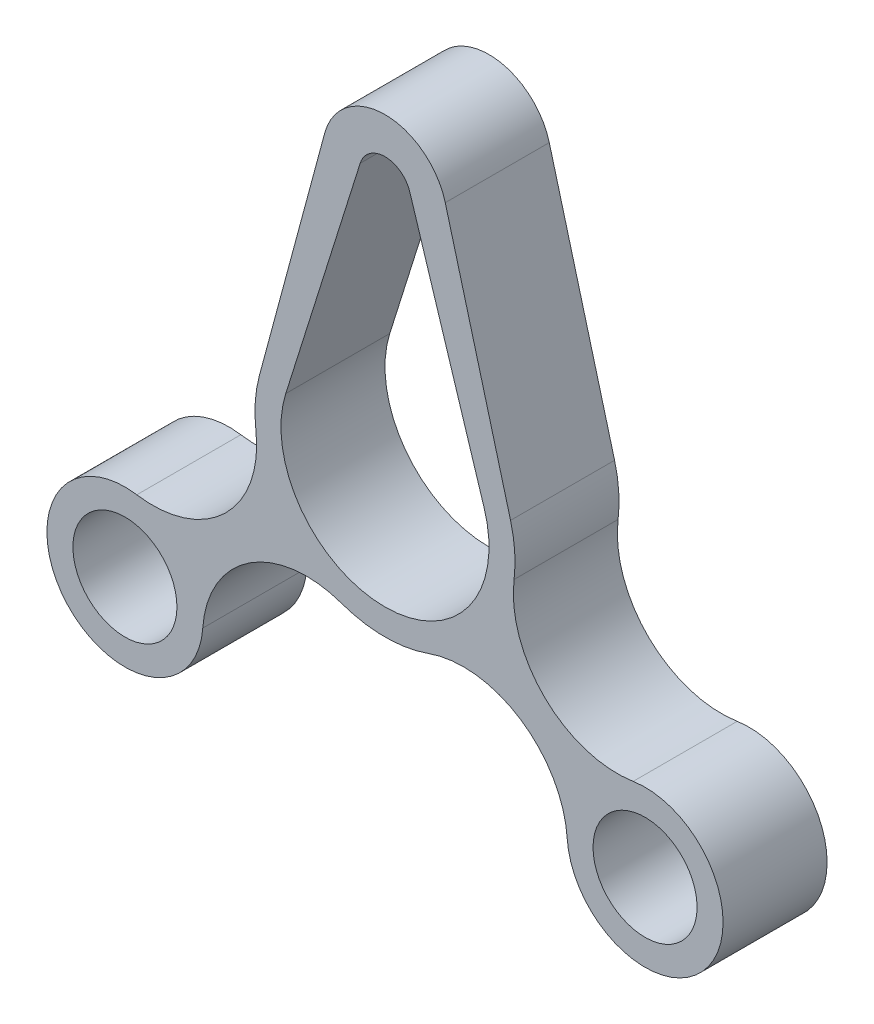
SolidWorks part; units mm, degrees
ref_plane "Front Plane" through (0, 0, 0) normal (0, 0, 1) x (1, 0, 0)
ref_plane "Top Plane" through (0, 0, 0) normal (0, 1, 0) x (1, 0, 0)
ref_plane "Right Plane" through (0, 0, 0) normal (1, 0, 0) x (0, 0, -1)
sketch "Sketch1" plane through (0, 0, 0) normal (0, 0, 1) x (1, 0, 0)
  line L0 (0, 0) -> (0, 40332.8036) construction
  line L1 (0, 0) -> (40332.8036, 0) construction
  line L2 (-24.1402, 6.5) -> (-11.5873, 53.12)
  line L3 (24.1402, 6.5) -> (11.5873, 53.12)
  line L4 (-19.0788, 6) -> (-4.7697, 51.5)
  line L5 (19.0788, 6) -> (4.7697, 51.5)
  arc A0 (-19.0788, 6) -> (19.0788, 6) centre (0, 0) ccw
  arc A1 (-24.1402, 6.5) -> (-24.8188, -3.0042) centre (0, 0) ccw
  circle A2 centre (-50, -40) radius 10
  arc A3 (-47.7174, -25.1747) -> (-35.0352, -41.0274) centre (-50, -40) ccw
  arc A4 (-47.7174, -25.1747) -> (-24.8188, -3.0042) centre (-44.6739, -5.4076) ccw
  arc A5 (4.7697, 51.5) -> (-4.7697, 51.5) centre (0, 50) ccw
  arc A6 (11.5873, 53.12) -> (-11.5873, 53.12) centre (0, 50) ccw
  arc A7 (-35.0352, -41.0274) -> (-8.379, -23.554) centre (-15.0822, -42.3973) cw
  circle A8 centre (50, -40) radius 10
  arc A9 (47.7174, -25.1747) -> (35.0352, -41.0274) centre (50, -40) cw
  arc A10 (35.0352, -41.0274) -> (8.379, -23.554) centre (15.0822, -42.3973) ccw
  arc A11 (47.7174, -25.1747) -> (24.8188, -3.0042) centre (44.6739, -5.4076) cw
  arc A12 (-8.379, -23.554) -> (8.379, -23.554) centre (0, 0) ccw
  arc A13 (24.8188, -3.0042) -> (24.1402, 6.5) centre (0, 0) ccw
  dimension "D1" = 40
  dimension "D2" = 50
  dimension "D3" = 40
  dimension "D5" = 20
  dimension "D6" = 30
  dimension "D7" = 20
  dimension "D8" = 10
  dimension "D9" = 24
  dimension "D11" = 20
  dimension "D4" = 50
  dimension "D10" = 50
extrude "Boss-Extrude1" add sketch "Sketch1" along normal mid plane 20
